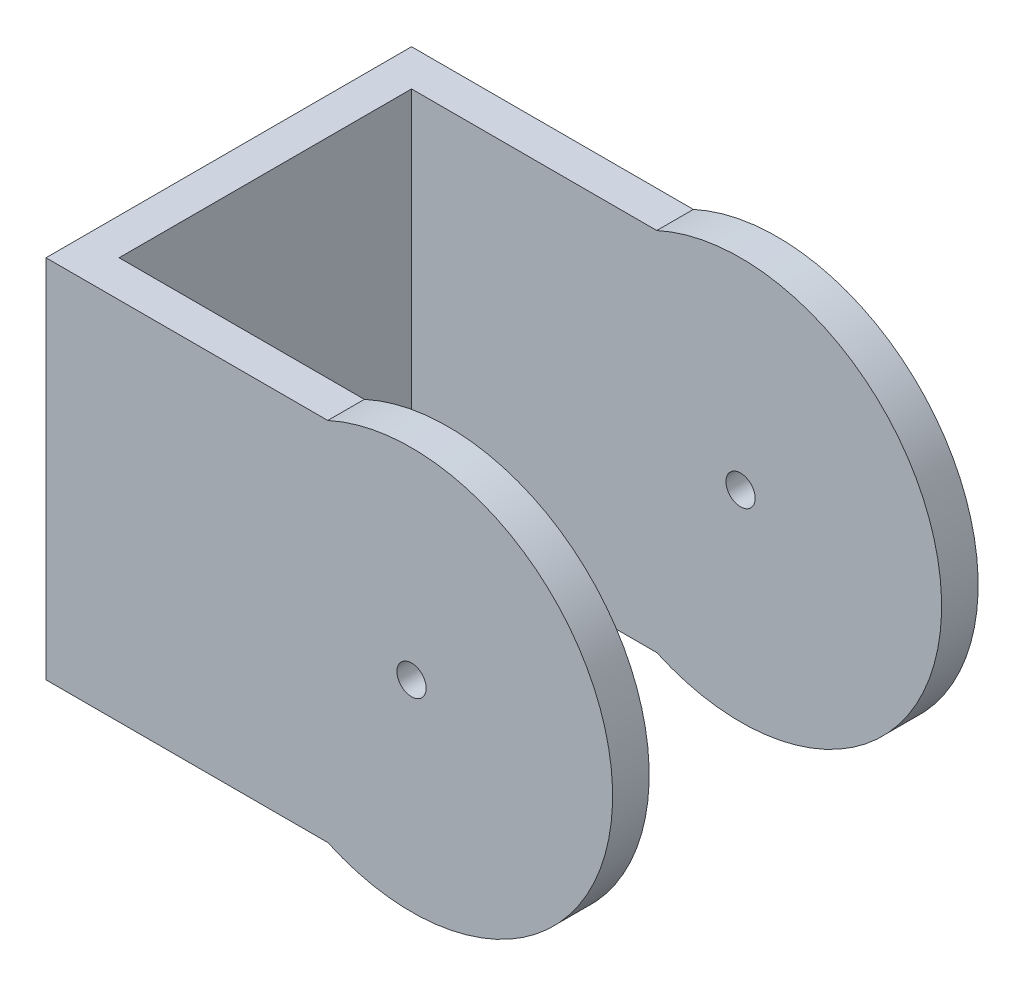
SolidWorks part; units mm, degrees
ref_plane "Front Plane" through (0, 0, 0) normal (0, 0, 1) x (1, 0, 0)
ref_plane "Top Plane" through (0, 0, 0) normal (0, 1, 0) x (1, 0, 0)
ref_plane "Right Plane" through (0, 0, 0) normal (1, 0, 0) x (0, 0, -1)
sketch "Sketch1" plane through (0, 0, 0) normal (0, 0, 1) x (1, 0, 0)
  line L0 (0, 0) -> (-5.5, 0)
  line L1 (-10, 5) -> (-10, -5)
  line L2 (-10, 5) -> (-2.2913, 5)
  line L3 (-10, -5) -> (-2.2913, -5)
  line L4 (0, 0) -> (0.4, 0) construction
  arc A0 (-2.2913, -5) -> (-2.2913, 5) centre (0, 0) ccw
  circle A1 centre (0, 0) radius 0.4
  dimension "D1" = 11
  dimension "D2" = 0.4
  dimension "D3" = 10
extrude "Boss-Extrude1" add sketch "Sketch1" along normal blind 10
sketch "Sketch2" plane through (-10, 0, 0) normal (-1, 0, 0) x (0, 0, 1)
  line L0 (0, 5) -> (0, -5) construction
  line L2 (0, 5) -> (0, -5) construction
  line L4 (10, 5) -> (10, -5) construction
  line L6 (5.3117, -5) -> (5.3117, -4) construction
  line L7 (10, -5) -> (0, -5) construction
  line L9 (9, 7.5) -> (9, -7.5)
  line L11 (1, -7.5) -> (1, 7.5)
  line L19 (1, 7.5) -> (9, 7.5)
  line L20 (1, -7.5) -> (9, -7.5)
  point P2 (0, 0)
  point P5 (1, 0)
  point P10 (9, 0)
  dimension "D1" = 1
  dimension "D2" = 15
  dimension "D3" = 1
  dimension "D4" = 1
  dimension "D5" = 15
extrude "Cut-Extrude2" cut sketch "Sketch2" against normal blind 19
sketch "Sketch3" plane through (-10, 0, 0) normal (-1, 0, 0) x (0, 0, 1)
  line L0 (0, 5) -> (10, 5)
  line L1 (10, 5) -> (10, -5)
  line L2 (10, -5) -> (0, -5)
  line L3 (0, -5) -> (0, 5)
extrude "Boss-Extrude2" add sketch "Sketch3" against normal blind 1
sketch "Sketch4" plane through (-10, 0, 0) normal (-1, 0, 0) x (0, 0, 1)
  line L0 (0, 5) -> (10, -5) construction
  line L1 (5, 0) -> (5.4, 0) construction
  circle A0 centre (5, 0) radius 0.4
  dimension "D1" = 0.4
extrude "Cut-Extrude3" cut sketch "Sketch4" against normal blind 2 contours A0
